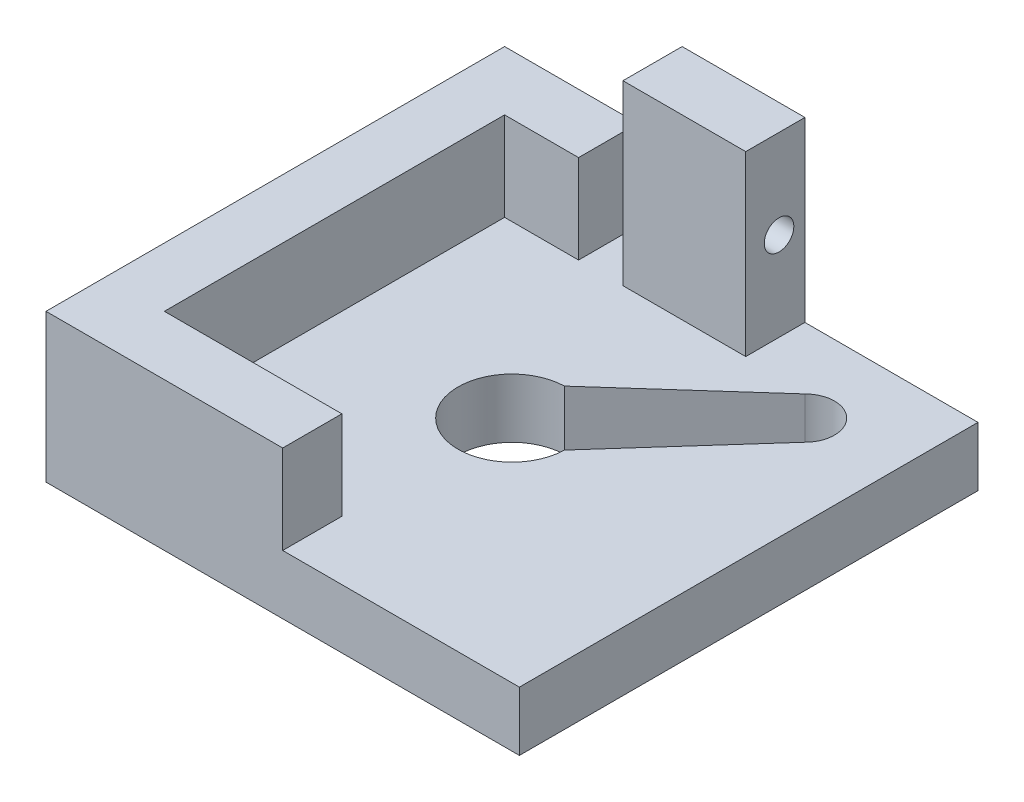
SolidWorks part; units mm, degrees
ref_plane "Front Plane" through (0, 0, 0) normal (0, 0, 1) x (1, 0, 0)
ref_plane "Top Plane" through (0, 0, 0) normal (0, 1, 0) x (1, 0, 0)
ref_plane "Right Plane" through (0, 0, 0) normal (1, 0, 0) x (0, 0, -1)
sketch "Sketch1" plane through (0, 0, 0) normal (0, 1, 0) x (1, 0, 0)
  line L1 (-16, -15.5) -> (16, -15.5)
  line L2 (-16, -15.5) -> (-16, 15.5)
  line L3 (-16, 15.5) -> (16, 15.5)
  line L4 (16, -15.5) -> (16, 15.5)
  line L5 (-16, -15.5) -> (16, 15.5) construction
  line L6 (-16, 15.5) -> (16, -15.5) construction
  point P0 (0, 0)
  dimension "D1" = 32
  dimension "D2" = 31
extrude "Boss-Extrude1" add sketch "Sketch1" along normal blind 4
sketch "Sketch2" plane through (0, 4, 0) normal (0, 1, 0) x (1, 0, 0)
  line L0 (-16, 15.5) -> (-16, -15.5)
  line L1 (-16, -15.5) -> (0, -15.5)
  line L2 (-16, -15.5) -> (16, -15.5) construction
  line L3 (0, -15.5) -> (0, -11.5)
  line L7 (-7, 11.5) -> (-12, 11.5)
  line L8 (-12, 11.5) -> (-12, -11.5)
  line L9 (-12, -11.5) -> (0, -11.5)
  line L10 (-16, 15.5) -> (-7, 15.5)
  line L11 (16, 15.5) -> (-16, 15.5) construction
  line L12 (-7, 15.5) -> (-7, 11.5)
  dimension "D1" = 4
  dimension "D2" = 4
  dimension "D3" = 5
  dimension "D4" = 4
  dimension "D5" = 31
  dimension "D6" = 9
  dimension "D7" = 16
extrude "Boss-Extrude2" add sketch "Sketch2" along normal blind 6
sketch "Sketch5" plane through (0, 4, 0) normal (0, 1, 0) x (1, 0, 0)
  line L0 (16, 15.5) -> (-7, 15.5) construction
  line L1 (-4, 11.5) -> (4.3, 11.5)
  line L2 (-4, 11.5) -> (-4, 15.5)
  line L3 (-4, 15.5) -> (4.3, 15.5)
  line L4 (4.3, 11.5) -> (4.3, 15.5)
  line L5 (-7, 11.5) -> (-7, 15.5) construction
  dimension "D1" = 3
  dimension "D2" = 8.3
  dimension "D3" = 4
extrude "Boss-Extrude3" add sketch "Sketch5" along normal blind 12
sketch "Sketch6" plane through (4.3, 0, 0) normal (1, 0, 0) x (0, 0, -1)
  line L0 (11.5, 16) -> (11.5, 4) construction
  line L2 (11.5, 16) -> (15.5, 16) construction
  circle A0 centre (13.75, 10) radius 1
  dimension "D1" = 2
  dimension "D2" = 2.25
  dimension "D3" = 6
extrude "Cut-Extrude7" cut sketch "Sketch6" against normal blind 5
sketch "Sketch4" plane through (0, 4, 0) normal (0, 1, 0) x (0.7071, 0, -0.7071)
  line L0 (0, 0) -> (0, 2.65) construction
  line L1 (0, 0) -> (0, -2.65) construction
  line L2 (0, 0) -> (16, 0) construction
  line L4 (0, -2.65) -> (2.51, -2.65) construction
  line L5 (2.51, 2.65) -> (14, 2)
  line L7 (0, 2.65) -> (2.51, 2.65) construction
  line L10 (16, 0) -> (14, 2) construction
  line L11 (16, 0) -> (14, -2) construction
  line L12 (2.51, -2.65) -> (14, -2)
  circle A0 centre (0, 0) radius 3.65
  arc A3 (2.51, 2.65) -> (2.51, -2.65) centre (0, 0) cw
  arc A4 (16, 0) -> (14, 2) centre (14, 0) ccw
  arc A5 (16, 0) -> (14, -2) centre (14, 0) cw
  dimension "D1" = 7.3
  dimension "D2" = 16
  dimension "D3" = 45
  dimension "D4" = 45
  dimension "D5" = 2
  dimension "D6" = 2.65
  dimension "D7" = 2.65
  dimension "D8" = 2
extrude "Cut-Extrude6" cut sketch "Sketch4" against normal blind 4
